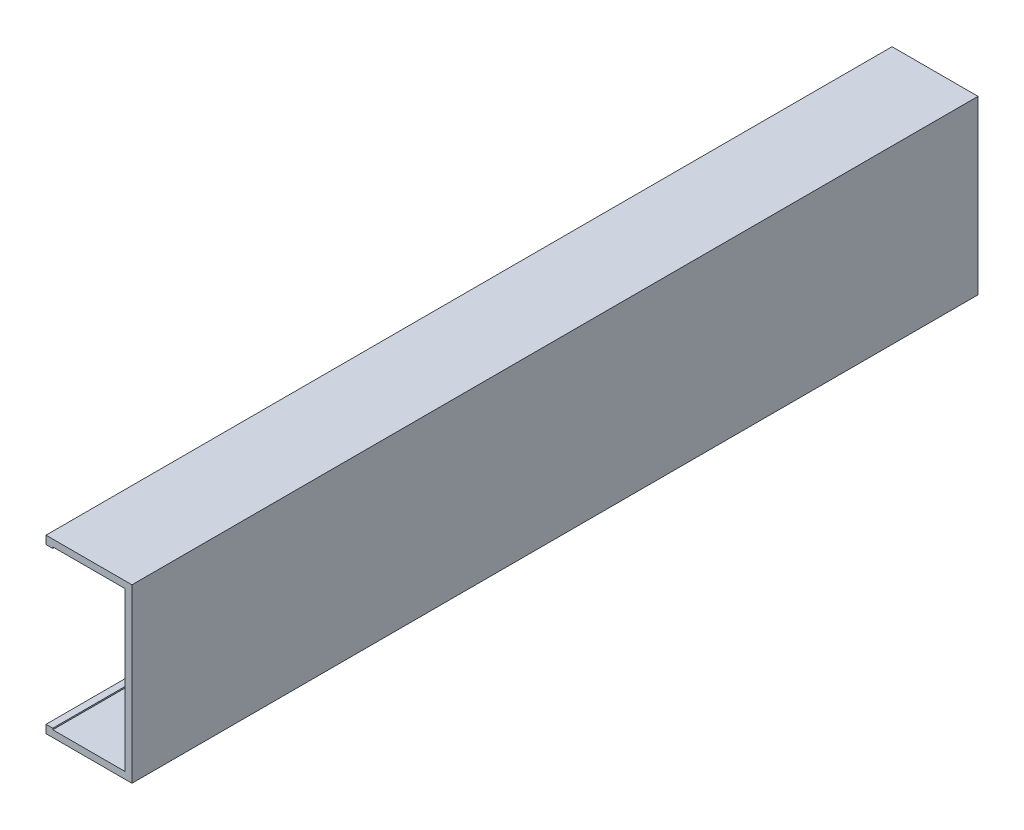
SolidWorks part; units mm, degrees
ref_plane "Front Plane" through (0, 0, 0) normal (0, 0, 1) x (1, 0, 0)
ref_plane "Top Plane" through (0, 0, 0) normal (0, 1, 0) x (1, 0, 0)
ref_plane "Right Plane" through (0, 0, 0) normal (1, 0, 0) x (0, 0, -1)
sketch "Sketch1" plane through (0, 0, 0) normal (0, 0, 1) x (1, 0, 0)
  line L0 (-10.7, 23.4) -> (10.7, 23.4)
  line L1 (-12.7, -25.4) -> (12.7, -25.4)
  line L2 (-12.7, -25.4) -> (-12.7, 25.4)
  line L3 (-12.7, 25.4) -> (12.7, 25.4)
  line L4 (12.7, -25.4) -> (12.7, 25.4)
  line L5 (-12.7, -25.4) -> (12.7, 25.4) construction
  line L6 (-12.7, 25.4) -> (12.7, -25.4) construction
  line L7 (10.7, -23.4) -> (10.7, 23.4)
  line L8 (-10.7, -23.4) -> (10.7, -23.4)
  line L9 (-10.7, -23.4) -> (-10.7, 23.4)
  point P0 (0, 0)
  dimension "D1" = 25.4
  dimension "D2" = 50.8
  dimension "D3" = 2
extrude "Boss-Extrude1" add sketch "Sketch1" along normal blind 250
sketch "Sketch2" plane through (-12.7, 0, 0) normal (-1, 0, 0) x (0, 0, 1)
  line L0 (0, 0) -> (250, 0) construction
  line L1 (250, 25.4) -> (250, -25.4) construction
  line L2 (0, 25.4) -> (0, -25.4) construction
  line L3 (0, -23) -> (80, -23)
  line L4 (0, -23) -> (0, 23)
  line L5 (0, 23) -> (80, 23)
  line L6 (80, -23) -> (80, 23)
  line L7 (0, -23) -> (80, 23) construction
  line L8 (0, 23) -> (80, -23) construction
  line L9 (125, 25.4) -> (125, -25.4) construction
  line L10 (250, 25.4) -> (0, 25.4) construction
  line L11 (250, -25.4) -> (0, -25.4) construction
  line L12 (250, 23) -> (170, 23)
  line L13 (170, -23) -> (170, 23)
  line L14 (250, -23) -> (170, -23)
  line L15 (250, -23) -> (250, 23)
  point P5 (40, 0)
  dimension "D1" = 40
  dimension "D2" = 46
  dimension "D3" = 80
extrude "Cut-Extrude1" cut sketch "Sketch2" against normal blind 20
